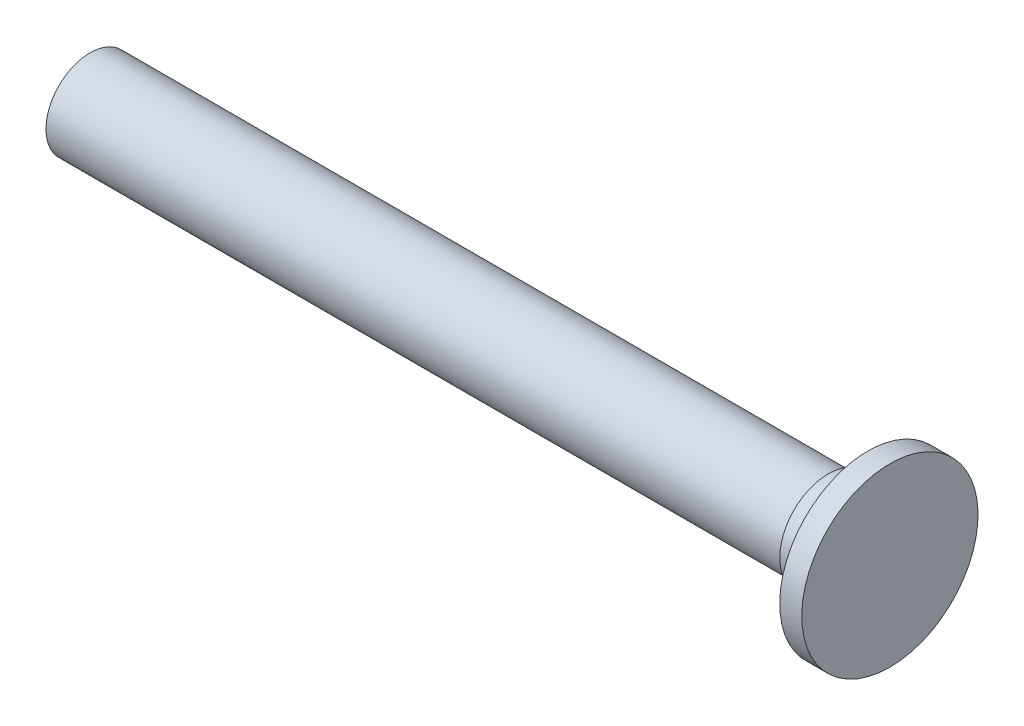
SolidWorks part; units mm, degrees
ref_plane "前视基准面" through (0, 0, 0) normal (0, 0, 1) x (1, 0, 0)
ref_plane "上视基准面" through (0, 0, 0) normal (0, 1, 0) x (1, 0, 0)
ref_plane "右视基准面" through (0, 0, 0) normal (1, 0, 0) x (0, 0, -1)
sketch "草图1" plane through (0, 0, 0) normal (0, 0, 1) x (1, 0, 0)
  line L0 (68.0286, 0) -> (21.5723, 0) construction
  line L1 (0, 55.3368) -> (0, -43.0627) construction
  line L2 (0, 0) -> (0, 20)
  line L3 (0, 20) -> (-5, 20)
  line L4 (-5, 20) -> (-5, 11)
  line L5 (-5, 11) -> (-14, 11)
  line L6 (-14, 11) -> (-14, 10)
  line L7 (-14, 10) -> (-181.5, 10)
  line L8 (-181.5, 10) -> (-181.5, 0)
  line L9 (0, 0) -> (-181.5, 0)
revolve "旋转1" add sketch "草图1" angle 360 about L0
